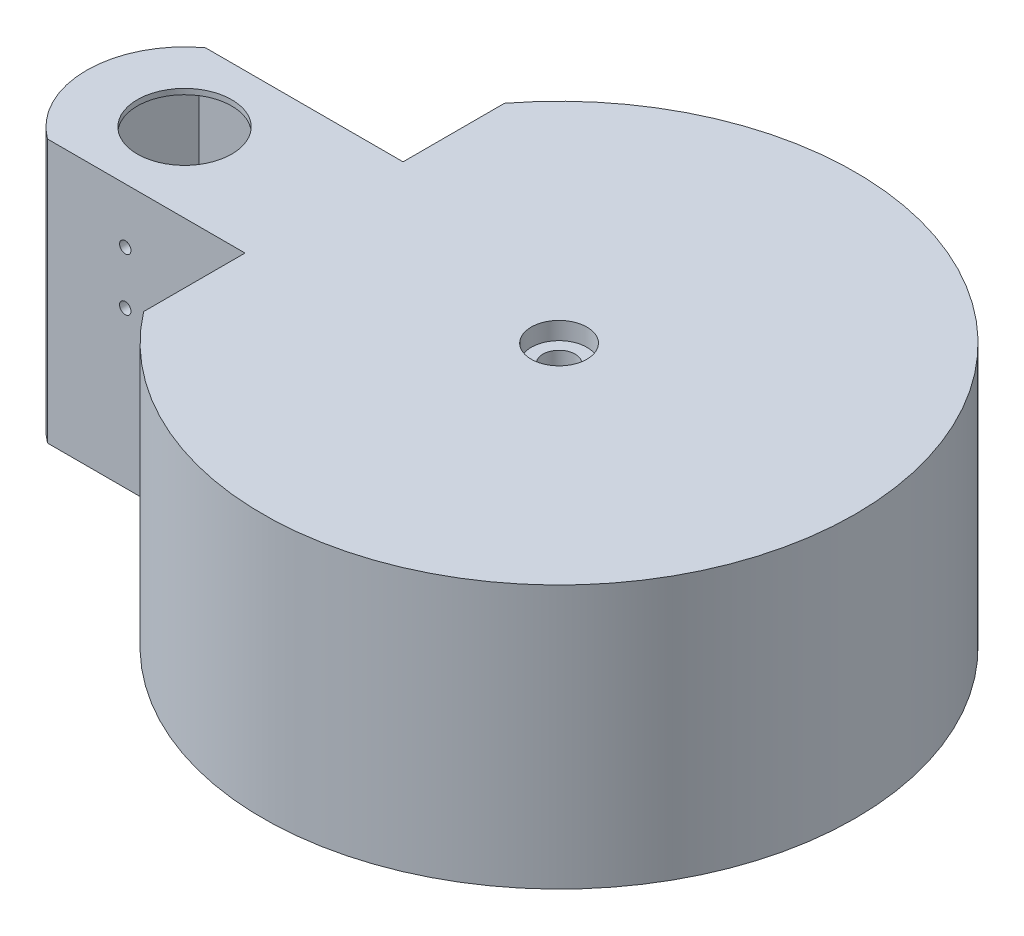
SolidWorks part; units mm, degrees
ref_plane "Plan de face" through (0, 0, 0) normal (0, 0, 1) x (1, 0, 0)
ref_plane "Plan de dessus" through (0, 0, 0) normal (0, 1, 0) x (1, 0, 0)
ref_plane "Plan de droite" through (0, 0, 0) normal (1, 0, 0) x (0, 0, -1)
sketch "Esquisse1" plane through (0, 0, 0) normal (0, 1, 0) x (1, 0, 0)
  line L0 (-85.33, 0) -> (0, 0) construction
  line L1 (-67.5, 22.9039) -> (-67.5, -22.4384) construction
  line L2 (-63, 20.67) -> (-63, -23.3426) construction
  line L3 (-98.5447, 18) -> (-53.5447, 18)
  line L4 (-53.5447, 18) -> (-53.5447, 41.1)
  line L5 (-65.0557, -18) -> (-72.1153, -18)
  line L6 (-98.5447, -18) -> (-53.5447, -18)
  line L7 (-53.5447, -18) -> (-53.5447, -41.1)
  circle A0 centre (0, 0) radius 67.5
  circle A1 centre (0, 0) radius 3.675
  circle A2 centre (-85.33, 0) radius 22.33
  circle A3 centre (-85.33, 0) radius 10.75
  point P10 (-63, 0)
  point P12 (-67.5, 0)
  point P17 (-66.4411, 11.9095)
  dimension "D1" = 135
  dimension "D2" = 7.35
  dimension "D3" = 4.5
  dimension "D4" = 44.66
  dimension "D8" = 21.5
  dimension "D5" = 45
  dimension "D6" = 18
  dimension "D7" = 18
extrude "Boss.-Extru.1" add sketch "Esquisse1" along normal blind 60 contours A0 A2 | A0 A2 | A2 A0 A1 | A2 A0 L3 | A2 L5 A0
sketch "Esquisse2" plane through (0, 0, 0) normal (0, -1, 0) x (1, 0, 0)
  line L1 (-96.58, 14.5) -> (-46.58, 14.5)
  line L2 (-96.58, 14.5) -> (-96.58, -14.5)
  line L3 (-96.58, -14.5) -> (-46.58, -14.5)
  line L4 (-46.58, 14.5) -> (-46.58, -14.5)
  point P4 (-96.58, 0)
  point P7 (-85.33, 0)
  dimension "D1" = 29
  dimension "D2" = 50
  dimension "D3" = 11.25
extrude "Enlèv. mat.-Extru.1" cut sketch "Esquisse2" against normal offset from surface (58.75 mm away) 1.25 up to face at (-49.8898, 60, 0)
hole_wizard "Dégagement M21" positions "Esquisse3D1" profile "Esquisse3" hole size "M2" standard "Ansi Metric" end condition through all
sketch3d "Esquisse3D1"
  line L1 (-85.33, 60, 0) -> (-85.33, 60, -18) construction
  line L2 (-85.33, 60, 0) -> (-85.33, 58.75, 0) construction
  line L3 (-85.33, 60, 0) -> (-85.33, 0, 0) construction
  line L4 (-98.5447, 60, -18) -> (-53.5447, 60, -18) construction
  line L5 (-85.33, 60, -18) -> (-85.33, 3.9282, -18) construction
  point P0 (-56.83, 47.5, -18)
  point P2 (-80.83, 47.5, -18)
  point P4 (-80.83, 35.5, -18)
  point P6 (-56.83, 35.5, -18)
  dimension "D1" = 12
  dimension "D2" = 12.5
  dimension "D3" = 24
  dimension "D4" = 4.5
sketch "Esquisse3" plane through (-56.83, 47.5, -18) normal (1, 0, 0) x (0, 1, 0)
  line L0 (0, 0) -> (0, 85.5)
  line L1 (0, 85.5) -> (1.3, 85.5)
  line L2 (1.3, 85.5) -> (1.3, 0)
  line L5 (1.3, 0) -> (0, 0)
  line L11 (0, -6.35) -> (0, 107.95) construction
  dimension "Diamètre du perçage jusqu'au prochain" = 2.6
  dimension "Profondeur du perçage jusqu'au prochain" = 85.5
sketch "Esquisse4" plane through (0, 0, 0) normal (0, -1, 0) x (1, 0, 0)
  circle A0 centre (0, 0) radius 6.35
  dimension "D1" = 12.7
extrude "Enlèv. mat.-Extru.2" cut sketch "Esquisse4" against normal blind 4
sketch "Esquisse5" plane through (0, 60, 0) normal (0, 1, 0) x (1, 0, 0)
  circle A0 centre (0, 0) radius 6.35
  dimension "D1" = 12.7
extrude "Enlèv. mat.-Extru.3" cut sketch "Esquisse5" against normal blind 4
